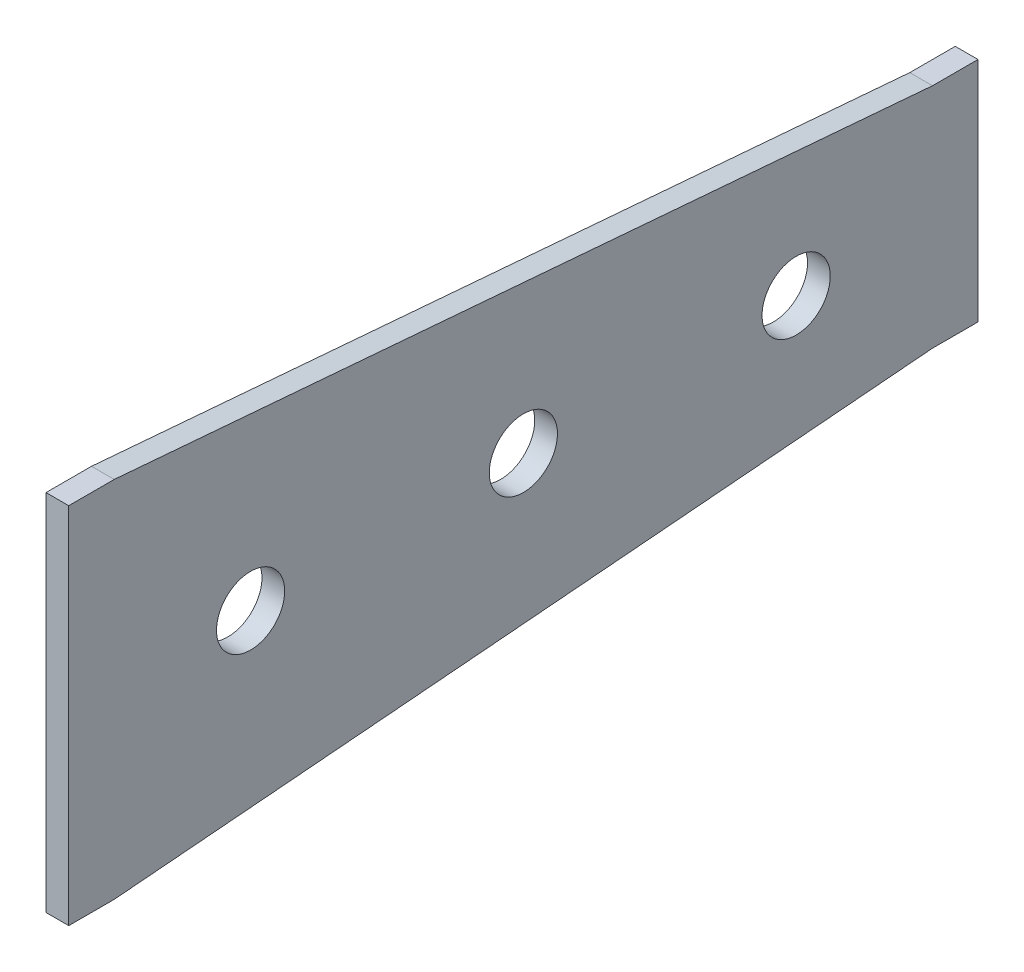
SolidWorks part; units mm, degrees
ref_plane "Front Plane" through (0, 0, 0) normal (0, 0, 1) x (1, 0, 0)
ref_plane "Top Plane" through (0, 0, 0) normal (0, 1, 0) x (1, 0, 0)
ref_plane "Right Plane" through (0, 0, 0) normal (1, 0, 0) x (0, 0, -1)
sketch "Sketch1" plane through (0, 0, 0) normal (1, 0, 0) x (0, 0, -1)
  line L0 (-60, 0) -> (60, 0) construction
  line L1 (100, -25) -> (100, 25)
  line L2 (-100, 40) -> (-100, -40)
  line L5 (-100, 40) -> (-90, 40)
  line L7 (-100, -40) -> (-90, -40)
  line L9 (-100, 0) -> (100, 0) construction
  line L10 (100, 25) -> (90, 25)
  line L11 (90, 25) -> (-90, 40)
  line L12 (100, -25) -> (90, -25)
  line L13 (90, -25) -> (-90, -40)
  circle A0 centre (0, 0) radius 7.5
  circle A1 centre (-60, 0) radius 7.5
  circle A2 centre (60, 0) radius 7.5
  point P10 (0, 0)
  point P13 (-100, 0)
  point P16 (100, 0)
  dimension "D1" = 15
  dimension "D3" = 200
  dimension "D2" = 120
  dimension "D5" = 50
  dimension "D6" = 80
  dimension "D7" = 10
extrude "Boss-Extrude1" add sketch "Sketch1" along normal mid plane 5
